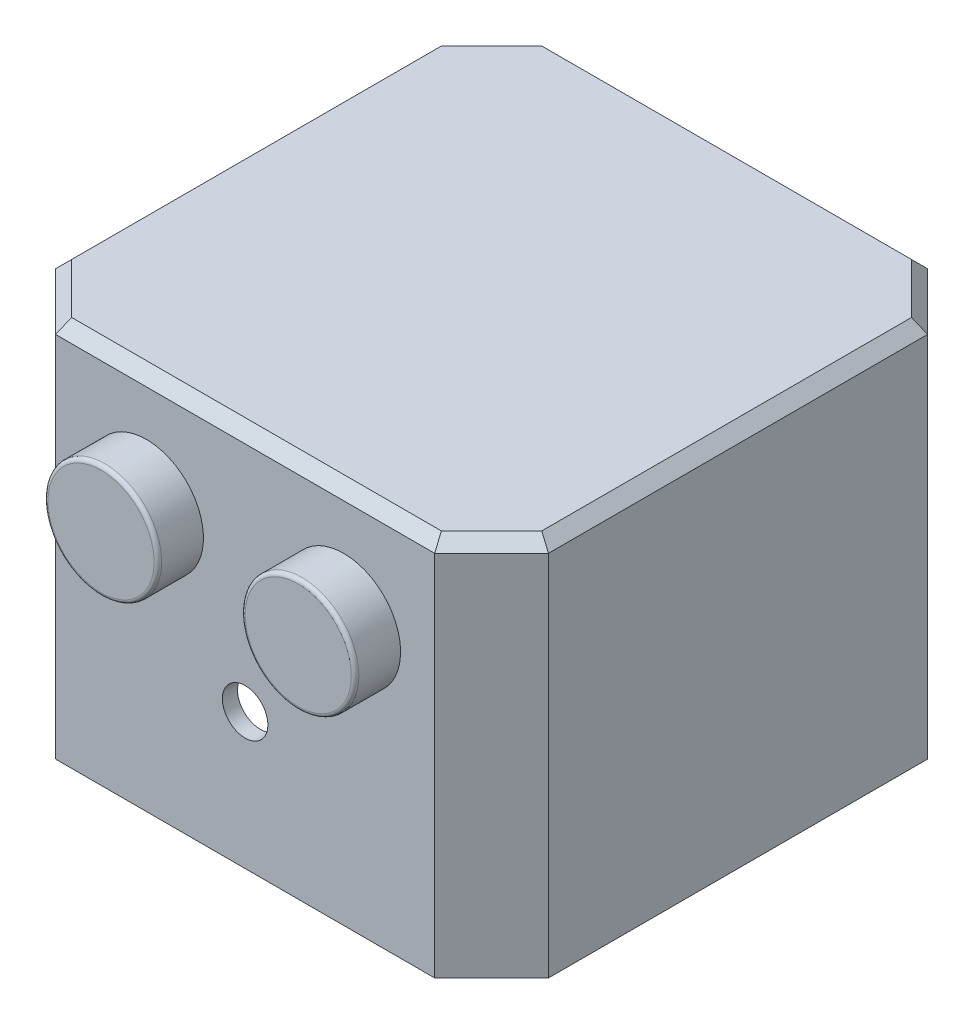
SolidWorks part; units mm, degrees
ref_plane "Alzado" through (0, 0, 0) normal (0, 0, 1) x (1, 0, 0)
ref_plane "Planta" through (0, 0, 0) normal (0, 1, 0) x (1, 0, 0)
ref_plane "Vista lateral" through (0, 0, 0) normal (1, 0, 0) x (0, 0, -1)
sketch "Croquis1" plane through (0, 0, 0) normal (0, 1, 0) x (1, 0, 0)
  line L1 (-25, -32.5) -> (25, -32.5)
  line L3 (-25, 32.5) -> (25, 32.5)
  line L5 (-25, -32.5) -> (25, 32.5) construction
  line L6 (-25, 32.5) -> (25, -32.5) construction
  line L10 (32.5, 25) -> (32.5, -25)
  line L11 (25, -32.5) -> (32.5, -25)
  line L12 (32.5, 25) -> (25, 32.5)
  line L13 (-32.5, 25) -> (-32.5, -25)
  line L14 (-32.5, -25) -> (-25, -32.5)
  line L15 (-32.5, 25) -> (-25, 32.5)
  point P0 (0, 0)
  point P10 (0, 32.5)
  dimension "D1" = 65
  dimension "D2" = 65
  dimension "D3" = 50
  dimension "D4" = 50
  dimension "D5" = 25
  dimension "D6" = 25
extrude "Saliente-Extruir1" add sketch "Croquis1" along normal blind 50
shell "Vaciado2" thickness 2
chamfer "Chaflán3" distance 1.5 angle 45 8 edges at (0, 50, -32.5) (32.5, 50, 0) (0, 50, 32.5) (-32.5, 50, 0) (-28.75, 50, 28.75) (28.75, 50, 28.75) (28.75, 50, -28.75) (-28.75, 50, -28.75)
sketch "Croquis2" plane through (0, 0, 32.5) normal (0, 0, 1) x (1, 0, 0)
  line L0 (0, 0) -> (0, 6.916) construction
  circle A0 centre (13, 35) radius 7.5
  circle A1 centre (-13, 35) radius 7.5
  dimension "D1" = 15
  dimension "D2" = 13
  dimension "D3" = 35
extrude "Saliente-Extruir2" add sketch "Croquis2" along normal blind 6
sketch "Croquis4" plane through (0, 0, 30.5) normal (0, 0, -1) x (-1, 0, 0)
  line L0 (0, 0) -> (0, 4.7403) construction
  line L1 (0, 0) -> (0, 6.916) construction
  circle A0 centre (-13, 35) radius 5
  circle A1 centre (13, 35) radius 5
  dimension "D1" = 10
extrude "Cortar-Extruir2" cut sketch "Croquis4" against normal blind 5
fillet "Redondeo1" radius 0.5 2 edges at (-20.5, 35, 38.5) (20.5, 35, 38.5)
sketch "Croquis5" plane through (0, 0, 32.5) normal (0, 0, 1) x (1, 0, 0)
  circle A0 centre (0, 17.9) radius 3
  dimension "D2" = 6
  dimension "D1" = 17.9
extrude "Cortar-Extruir3" cut sketch "Croquis5" against normal blind 10
sketch "Croquis6" plane through (0, 0, -32.5) normal (0, 0, -1) x (-1, 0, 0)
  line L1 (-21, 3) -> (-15, 3)
  line L2 (-21, 3) -> (-21, 9)
  line L3 (-21, 9) -> (-15, 9)
  line L4 (-15, 3) -> (-15, 9)
  line L5 (-21, 3) -> (-15, 9) construction
  line L6 (-21, 9) -> (-15, 3) construction
  point P0 (-18, 6)
  dimension "D1" = 18
  dimension "D2" = 6
  dimension "D3" = 6
  dimension "D4" = 3
extrude "Cortar-Extruir4" cut sketch "Croquis6" against normal blind 10
sketch "Croquis7" plane through (0, 0, 30.5) normal (0, 0, -1) x (-1, 0, 0)
  line L0 (24.1716, 0) -> (-24.1716, 0) construction
  line L1 (-13.58, 7.3) -> (-9.58, 7.3)
  line L2 (-13.58, 7.3) -> (-13.58, 11.3)
  line L3 (-13.58, 11.3) -> (-9.58, 11.3)
  line L4 (-9.58, 7.3) -> (-9.58, 11.3)
  line L5 (-13.58, 7.3) -> (-9.58, 11.3) construction
  line L6 (-13.58, 11.3) -> (-9.58, 7.3) construction
  line L8 (-13.58, 24.8) -> (-9.58, 24.8)
  line L9 (-13.58, 24.8) -> (-13.58, 28.8)
  line L10 (-13.58, 28.8) -> (-9.58, 28.8)
  line L11 (-9.58, 24.8) -> (-9.58, 28.8)
  line L12 (-13.58, 24.8) -> (-9.58, 28.8) construction
  line L13 (-13.58, 28.8) -> (-9.58, 24.8) construction
  line L14 (13.43, 11.3) -> (9.43, 7.3) construction
  line L15 (13.43, 7.3) -> (9.43, 11.3) construction
  line L16 (9.43, 7.3) -> (9.43, 11.3)
  line L17 (13.43, 11.3) -> (9.43, 11.3)
  line L18 (13.43, 7.3) -> (13.43, 11.3)
  line L19 (13.43, 7.3) -> (9.43, 7.3)
  line L20 (13.43, 28.8) -> (9.43, 24.8) construction
  line L21 (13.43, 24.8) -> (9.43, 28.8) construction
  line L22 (9.43, 24.8) -> (9.43, 28.8)
  line L23 (13.43, 28.8) -> (9.43, 28.8)
  line L24 (13.43, 24.8) -> (13.43, 28.8)
  line L25 (13.43, 24.8) -> (9.43, 24.8)
  point P0 (-11.58, 9.3)
  point P8 (-11.58, 26.8)
  point P13 (0, 0)
  point P15 (11.43, 9.3)
  point P16 (11.43, 26.8)
  point P20 (11.43, 9.3)
  point P25 (11.43, 26.8)
  dimension "D1" = 9.3
  dimension "D2" = 4
  dimension "D3" = 4
  dimension "D4" = 11.58
  dimension "D5" = 4
  dimension "D6" = 4
  dimension "D7" = 26.8
  dimension "D8" = 23.01
  dimension "D9" = 23.01
  dimension "D10" = 4
  dimension "D11" = 4
  dimension "D12" = 4
  dimension "D13" = 4
  dimension "D14" = 9.3
  dimension "D15" = 26.8
extrude "Saliente-Extruir3" add sketch "Croquis7" along normal blind 1
sketch "Croquis8" plane through (0, 0, 29.5) normal (0, 0, -1) x (-1, 0, 0)
  line L0 (0, 0) -> (0, 4.8013) construction
  line L1 (24.1716, 0) -> (-24.1716, 0) construction
  circle A0 centre (-11.505, 9.3) radius 1.1
  circle A1 centre (-11.505, 26.8) radius 1.1
  circle A2 centre (11.505, 9.3) radius 1.1
  circle A3 centre (11.505, 26.8) radius 1.1
  dimension "D1" = 2.2
  dimension "D2" = 2.2
  dimension "D3" = 23.01
  dimension "D4" = 23.01
